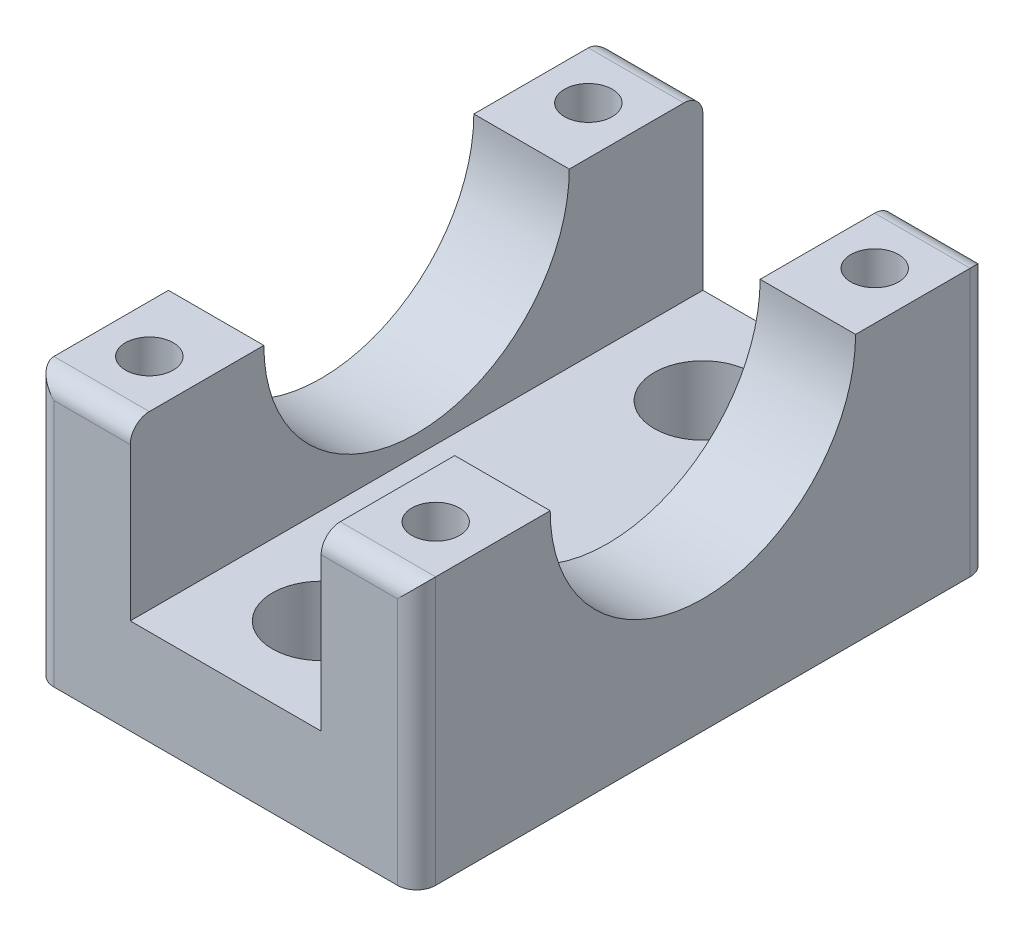
SolidWorks part; units mm, degrees
ref_plane "Front Plane" through (0, 0, 0) normal (0, 0, 1) x (1, 0, 0)
ref_plane "Top Plane" through (0, 0, 0) normal (0, 1, 0) x (1, 0, 0)
ref_plane "Right Plane" through (0, 0, 0) normal (1, 0, 0) x (0, 0, -1)
sketch "Sketch1" plane through (0, 0, 0) normal (0, 1, 0) x (1, 0, 0)
  line L1 (-10, -15) -> (10, -15)
  line L2 (-10, -15) -> (-10, 15)
  line L3 (-10, 15) -> (10, 15)
  line L4 (10, -15) -> (10, 15)
  line L5 (-10, -15) -> (10, 15) construction
  line L6 (-10, 15) -> (10, -15) construction
  point P0 (0, 0)
  dimension "D1" = 20
  dimension "D2" = 30
extrude "Boss-Extrude1" add sketch "Sketch1" along normal blind 5
sketch "Sketch2" plane through (0, 5, 0) normal (0, 1, 0) x (1, 0, 0)
  line L0 (0, -1000) -> (0, 49000) construction
  line L1 (10, 15) -> (-10, 15) construction
  line L2 (-10, -15) -> (10, -15) construction
  circle A0 centre (0, 10) radius 2.55
  circle A1 centre (0, -10) radius 2.55
  dimension "D1" = 5.1
  dimension "D2" = 5.1
  dimension "D3" = 5
  dimension "D4" = 5
extrude "Cut-Extrude1" cut sketch "Sketch2" against normal through all
sketch "Sketch3" plane through (0, 5, 0) normal (0, 1, 0) x (1, 0, 0)
  line L0 (10, 15) -> (-10, 15) construction
  line L1 (-10, -15) -> (-5, -15)
  line L2 (-10, -15) -> (-10, 15)
  line L3 (-10, 15) -> (-5, 15)
  line L4 (-5, -15) -> (-5, 15)
  dimension "D1" = 5
extrude "Boss-Extrude2" add sketch "Sketch3" along normal blind 9
sketch "Sketch4" plane through (-10, 0, 0) normal (-1, 0, 0) x (0, 0, 1)
  line L0 (-15, 14) -> (15, 14) construction
  circle A0 centre (0, 14) radius 8
  dimension "D1" = 16
extrude "Cut-Extrude2" cut sketch "Sketch4" against normal through all
sketch "Sketch5" plane through (0, 14, 0) normal (0, 1, 0) x (1, 0, 0)
  line L0 (-7.5, 15) -> (-7.5, 8) construction
  line L1 (-5, 15) -> (-10, 15) construction
  line L2 (-10, 8) -> (-5, 8) construction
  line L3 (-7.5, -8) -> (-7.5, -15) construction
  line L4 (-5, -8) -> (-10, -8) construction
  line L5 (-10, -15) -> (-5, -15) construction
  circle A0 centre (-7.5, 11.5) radius 1.25
  circle A1 centre (-7.5, -11.5) radius 1.25
  dimension "D1" = 2.5
  dimension "D2" = 2.5
extrude "Cut-Extrude3" cut sketch "Sketch5" against normal blind 10
mirror "Mirror1" about plane through (0, 0, 0) normal (1, 0, 0) of "Cut-Extrude3", "Cut-Extrude2", "Boss-Extrude2"
fillet "Fillet1" radius 1 8 edges at (-10, 7, -15) (10, 7, -15) (10, 7, 15) (-10, 7, 15) (-7.5, 14, -15) (7.5, 14, -15) (7.5, 14, 15) (-7.5, 14, 15)
